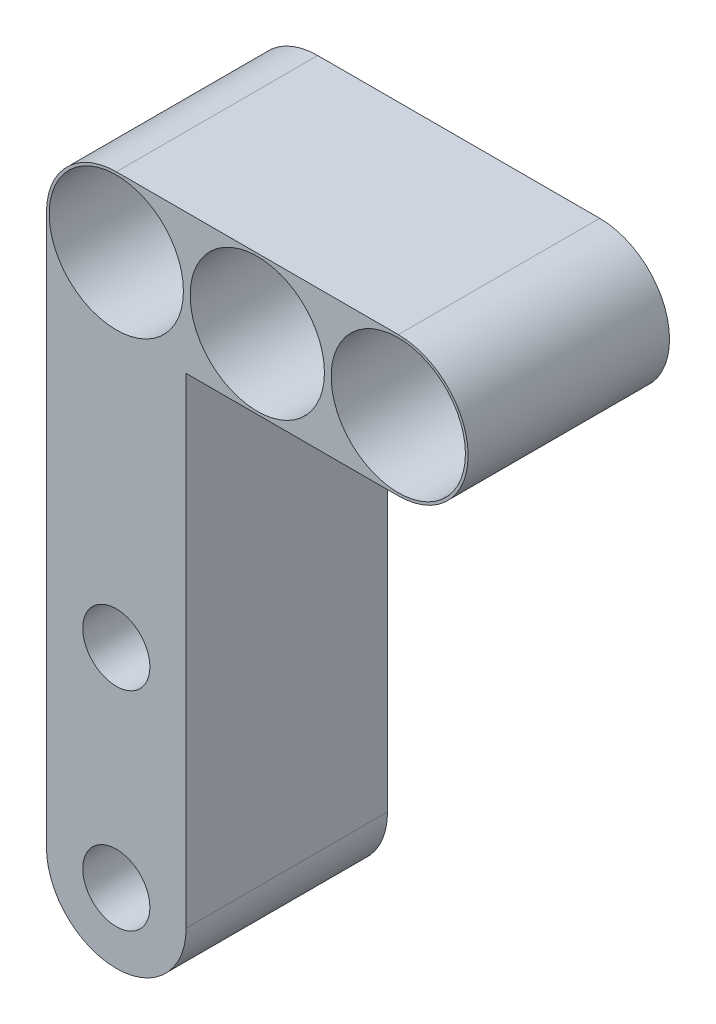
SolidWorks part; units mm, degrees
ref_plane "Front Plane" through (0, 0, 0) normal (0, 0, 1) x (1, 0, 0)
ref_plane "Top Plane" through (0, 0, 0) normal (0, 1, 0) x (1, 0, 0)
ref_plane "Right Plane" through (0, 0, 0) normal (1, 0, 0) x (0, 0, -1)
sketch "Sketch1" plane through (0, 0, 0) normal (0, 0, 1) x (1, 0, 0)
  line L0 (-0.52, 0) -> (-0.52, -4.0984)
  line L1 (0, 0.52) -> (2.1, 0.52)
  line L2 (0.52, -4.0984) -> (0.52, -0.52)
  line L3 (0.52, -0.52) -> (2.1, -0.52)
  circle A0 centre (0, 0) radius 0.5
  circle A1 centre (0, 0) radius 0.52
  circle A2 centre (1.05, 0) radius 0.52
  circle A3 centre (1.05, 0) radius 0.5
  circle A4 centre (2.1, 0) radius 0.52
  circle A5 centre (2.1, 0) radius 0.5
  circle A6 centre (0, -2.5484) radius 0.52
  circle A7 centre (0, -2.5484) radius 0.25
  circle A8 centre (0, -4.0984) radius 0.52
  circle A9 centre (0, -4.0984) radius 0.25
  dimension "D1" = 3
  dimension "D2" = 2
extrude "Boss-Extrude1" add sketch "Sketch1" along normal blind 1.5 contours A6 L2 L3 A2 L1 A1 L0 | A4 L1 A2 L3 | A4 A5 | A1 A0 | A2 A3 | A8 L2 A6 L0 | A6 A7 | A8 A9
